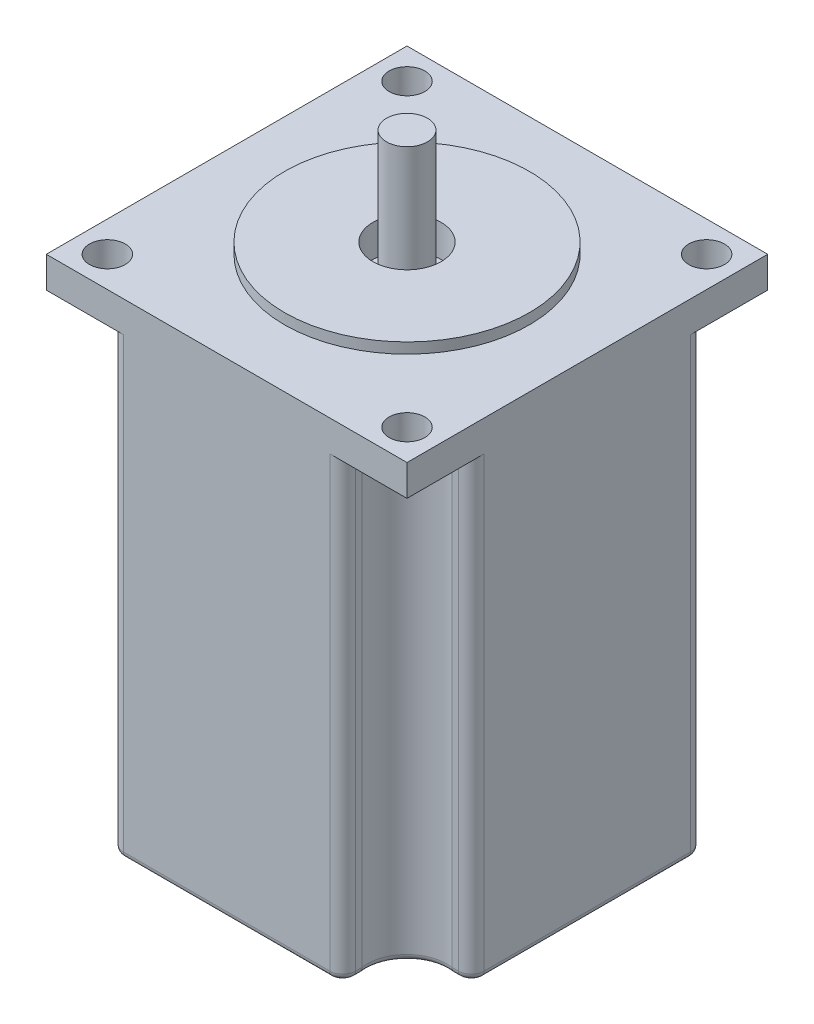
SolidWorks part; units mm, degrees
ref_plane "Plano frontal" through (0, 0, 0) normal (0, 0, 1) x (1, 0, 0)
ref_plane "Plano superior" through (0, 0, 0) normal (0, 1, 0) x (1, 0, 0)
ref_plane "Plano direito" through (0, 0, 0) normal (1, 0, 0) x (0, 0, -1)
sketch "Esboço1" plane through (0, 0, 0) normal (0, 1, 0) x (1, 0, 0)
  line L0 (28.05, 28.05) -> (-28.05, -28.05) construction
  line L1 (-28.05, 28.05) -> (28.05, 28.05)
  line L2 (-28.05, 28.05) -> (-28.05, -28.05)
  line L3 (-28.05, -28.05) -> (28.05, -28.05)
  line L4 (28.05, 28.05) -> (28.05, -28.05)
  dimension "D1" = 56.1
  dimension "D2" = 56.1
extrude "Ressalto-extrusão1" add sketch "Esboço1" along normal blind 75.5
sketch "Esboço2" plane through (0, 75.5, 0) normal (0, 1, 0) x (1, 0, 0)
  circle A0 centre (0, 0) radius 19.035
  dimension "D1" = 38.07
extrude "Ressalto-extrusão2" add sketch "Esboço2" along normal blind 1.65
sketch "Esboço3" plane through (0, 77.15, 0) normal (0, 1, 0) x (1, 0, 0)
  circle A0 centre (0, 0) radius 5.3
  dimension "D1" = 10.6
extrude "Corte-extrusão1" cut sketch "Esboço3" against normal blind 5
sketch "Esboço4" plane through (0, 72.15, 0) normal (0, 1, 0) x (1, 0, 0)
  circle A0 centre (0, 0) radius 3.185
  dimension "D1" = 6.37
extrude "Ressalto-extrusão3" add sketch "Esboço4" along normal blind 20.08
sketch "Esboço5" plane through (0, 0, 0) normal (0, -1, 0) x (1, 0, 0)
  line L0 (-28.05, 0) -> (28.05, 0) construction
  line L1 (-28.05, -28.05) -> (-28.05, 28.05) construction
  line L2 (28.05, 28.05) -> (28.05, -28.05) construction
  line L3 (0, 28.05) -> (0, -28.05) construction
  line L4 (-28.05, 28.05) -> (28.05, 28.05) construction
  line L5 (28.05, -28.05) -> (-28.05, -28.05) construction
  line L6 (-28.05, 18.05) -> (-28.05, -18.05)
  line L7 (-18.05, 28.05) -> (18.05, 28.05)
  line L8 (28.05, 18.05) -> (28.05, -18.05)
  line L9 (-18.05, -28.05) -> (18.05, -28.05)
  line L10 (-28.05, -18.05) -> (-25.05, -18.05)
  line L11 (-18.05, 28.05) -> (-18.05, 25.05)
  line L12 (-28.05, 18.05) -> (-25.05, 18.05)
  line L13 (18.05, 28.05) -> (18.05, 25.05)
  line L14 (-18.05, -25.05) -> (18.05, -25.05) construction
  line L15 (-25.05, -18.05) -> (-25.05, 18.05) construction
  line L16 (-18.05, 25.05) -> (18.05, 25.05) construction
  line L17 (25.05, 18.05) -> (25.05, -18.05) construction
  line L18 (25.05, 18.05) -> (28.05, 18.05)
  line L19 (-18.05, -25.05) -> (-18.05, -28.05)
  line L20 (25.05, -18.05) -> (28.05, -18.05)
  line L21 (18.05, -25.05) -> (18.05, -28.05)
  arc A0 (-18.05, 25.05) -> (-25.05, 18.05) centre (-24.1871, 24.1871) cw
  arc A1 (25.05, 18.05) -> (18.05, 25.05) centre (24.1871, 24.1871) cw
  arc A2 (18.05, -25.05) -> (25.05, -18.05) centre (24.1871, -24.1871) cw
  arc A3 (-25.05, -18.05) -> (-18.05, -25.05) centre (-24.1871, -24.1871) cw
  line M1 (-28.05, 28.05) -> (-28.05, -28.05)
  line M2 (-28.05, -28.05) -> (28.05, -28.05)
  line M3 (28.05, -28.05) -> (28.05, 28.05)
  line M4 (28.05, 28.05) -> (-28.05, 28.05)
  dimension "D9" = 6.1975
  dimension "D10" = 6.1975
  dimension "D11" = 6.1975
  dimension "D12" = 6.1975
  dimension "D2" = 10
  dimension "D3" = 10
  dimension "D4" = 10
  dimension "D5" = 3
  dimension "D6" = 3
  dimension "D7" = 3
  dimension "D8" = 3
  dimension "D13" = 10
  dimension "D14" = 10
  dimension "D15" = 10
extrude "Corte-extrusão2" cut sketch "Esboço5" against normal blind 70.67 contours A1 L18 L13 M3 M4 | A0 L11 L12 M4 M1 | A3 L10 L19 M1 M2 | A2 L21 L20 M2 M3
sketch "Esboço6" plane through (0, 75.5, 0) normal (0, 1, 0) x (1, 0, 0)
  line L0 (-28.05, 28.05) -> (-28.05, -28.05) construction
  line L1 (28.05, 28.05) -> (-28.05, 28.05) construction
  line L2 (28.05, 0) -> (-28.05, 0) construction
  line L3 (28.05, -28.05) -> (28.05, 28.05) construction
  line L5 (-28.05, -28.05) -> (28.05, -28.05) construction
  line L6 (0, -28.05) -> (0, 28.05) construction
  circle A0 centre (-23.3, 23.3) radius 2.78
  circle A1 centre (-23.3, -23.3) radius 2.78
  circle A2 centre (23.3, 23.3) radius 2.78
  circle A3 centre (23.3, -23.3) radius 2.78
  dimension "D1" = 5.56
  dimension "D2" = 4.75
  dimension "D3" = 4.75
  dimension "D4" = 46.6
  dimension "D5" = 46.6
extrude "Corte-extrusão3" cut sketch "Esboço6" against normal up to surface (4.83 mm away) up to face at (-23.101, 70.67, -23.101)
sketch "Esboço7" plane through (0, 0, 0) normal (0, -1, 0) x (1, 0, 0)
  circle A0 centre (0, 0) radius 3.185
  dimension "D1" = 6.37
extrude "Corte-extrusão4" cut sketch "Esboço7" against normal blind 5
fillet "Filete1" radius 2 8 edges at (28.05, 35.335, -18.05) (18.05, 35.335, -28.05) (-18.05, 35.335, -28.05) (-28.05, 35.335, -18.05) (-28.05, 35.335, 18.05) (-18.05, 35.335, 28.05) (18.05, 35.335, 28.05) (28.05, 35.335, 18.05)
fillet "Filete2" radius 1 25 edges at (19.8048, 0, -19.8048) (18.05, 0, -25.55) (17.4642, 0, -27.4642) (0, 0, -28.05) (-17.4642, 0, -27.4642) (-18.05, 0, -25.55) (-19.8048, 0, -19.8048) (-25.55, 0, -18.05) (-27.4642, 0, -17.4642) (-28.05, 0, 0) (-27.4642, 0, 17.4642) (-25.55, 0, 18.05) (-19.8048, 0, 19.8048) (-18.05, 0, 25.55) (-17.4642, 0, 27.4642) (0, 0, 28.05) (17.4642, 0, 27.4642) (18.05, 0, 25.55) (19.8048, 0, 19.8048) (25.55, 0, 18.05) (27.4642, 0, 17.4642) (28.05, 0, 0) (27.4642, 0, -17.4642) (25.55, 0, -18.05) (0, 0, -3.185)
